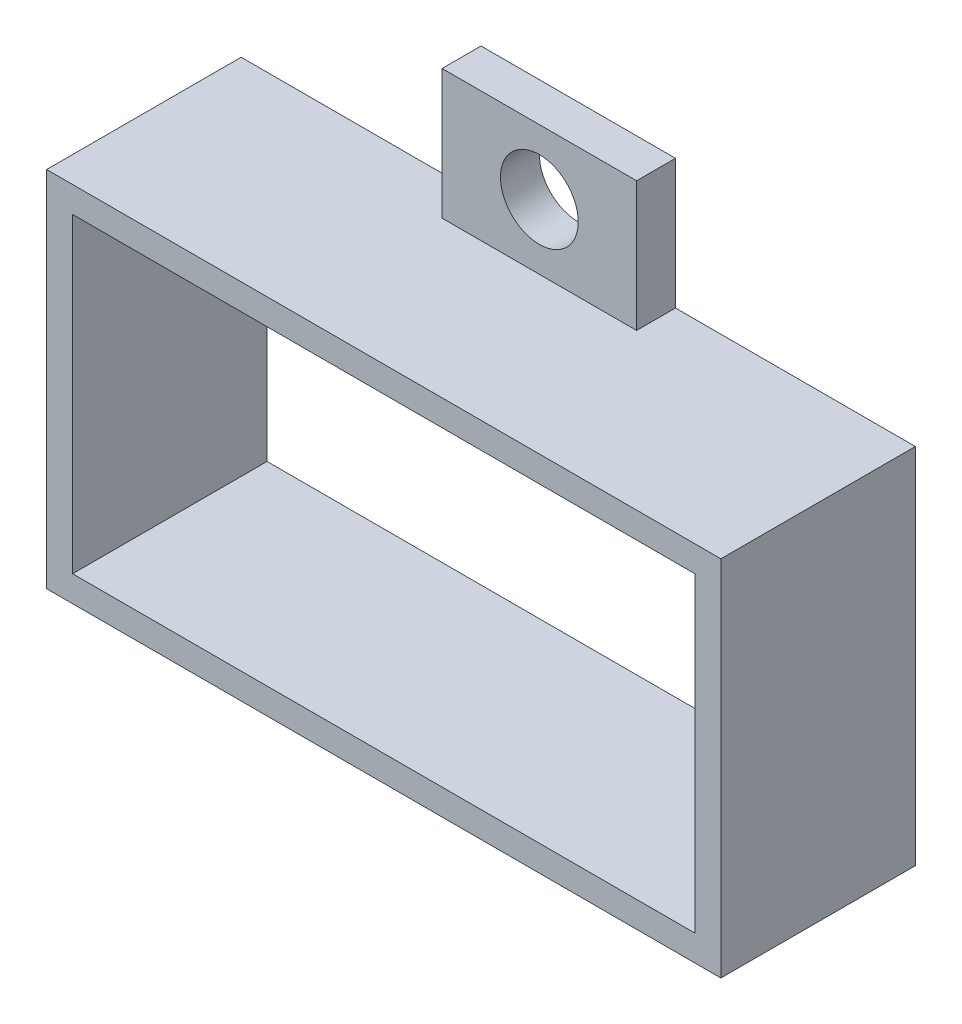
SolidWorks part; units mm, degrees
ref_plane "前基準面" through (0, 0, 0) normal (0, 0, 1) x (1, 0, 0)
ref_plane "上基準面" through (0, 0, 0) normal (0, 1, 0) x (1, 0, 0)
ref_plane "右基準面" through (0, 0, 0) normal (1, 0, 0) x (0, 0, -1)
sketch "草圖1" plane through (0, 0, 0) normal (0, 0, 1) x (1, 0, 0)
  line L1 (-26, 14) -> (26, 14)
  line L2 (-26, 14) -> (-26, -14)
  line L3 (-26, -14) -> (26, -14)
  line L4 (26, 14) -> (26, -14)
  line L5 (-26, 14) -> (26, -14) construction
  line L6 (-26, -14) -> (26, 14) construction
  line L7 (-24, 12) -> (24, 12)
  line L8 (-24, 12) -> (-24, -12)
  line L9 (-24, -12) -> (24, -12)
  line L10 (24, 12) -> (24, -12)
  line L11 (-24, 12) -> (24, -12) construction
  line L12 (-24, -12) -> (24, 12) construction
  point P0 (0, 0)
  point P6 (0, 0)
  dimension "D1" = 52
  dimension "D2" = 28
  dimension "D3" = 24
  dimension "D4" = 48
extrude "填料-伸長1" add sketch "草圖1" along normal blind 15
sketch "草圖2" plane through (0, 14, 0) normal (0, 1, 0) x (1, 0, 0)
  line L0 (26, 0) -> (-26, 0) construction
  line L1 (-7.5, 0) -> (7.5, 0)
  line L2 (-7.5, 0) -> (-7.5, -3)
  line L3 (-7.5, -3) -> (7.5, -3)
  line L4 (7.5, 0) -> (7.5, -3)
  line L5 (0, 0) -> (0, -3) construction
  dimension "D1" = 3
  dimension "D2" = 15
extrude "填料-伸長2" add sketch "草圖2" along normal blind 10
sketch "草圖3" plane through (0, 0, 3) normal (0, 0, 1) x (1, 0, 0)
  line L0 (26, 14) -> (-26, 14) construction
  line L1 (7.5, 24) -> (7.5, 14) construction
  circle A0 centre (0, 19) radius 3
  dimension "D3" = 6
  dimension "D1" = 5
  dimension "D2" = 7.5
extrude "除料-伸長1" cut sketch "草圖3" against normal blind 10
mirror "鏡射1" about plane through (0, 0, 0) normal (0, 1, 0) of "除料-伸長1", "填料-伸長2"
